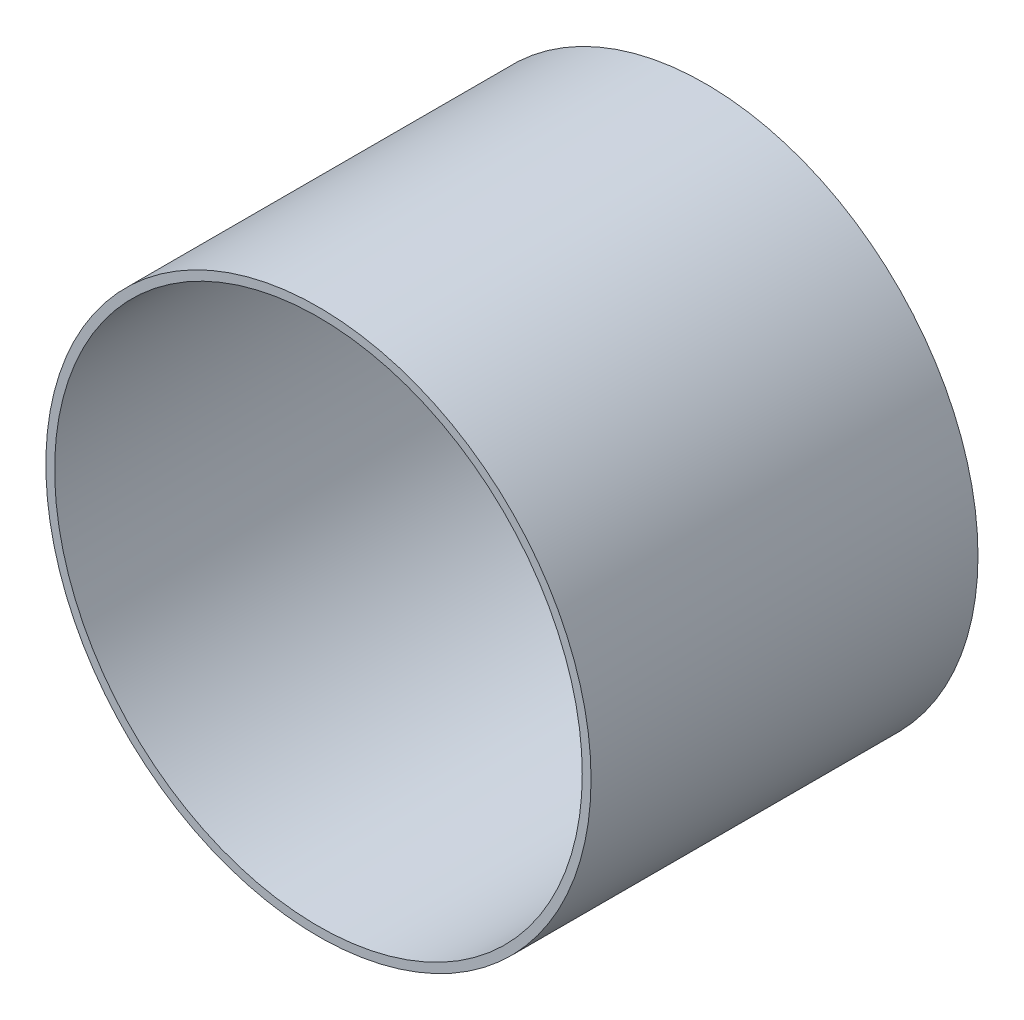
SolidWorks part; units mm, degrees
material "1023 Chapa de acero al carbono (SS)"
ref_plane "Alzado" through (0, 0, 0) normal (0, 0, 1) x (1, 0, 0)
ref_plane "Planta" through (0, 0, 0) normal (0, 1, 0) x (1, 0, 0)
ref_plane "Vista lateral" through (0, 0, 0) normal (1, 0, 0) x (0, 0, -1)
sketch "Croquis1" plane through (0, 0, 0) normal (0, 0, 1) x (1, 0, 0)
  circle A0 centre (0, 0) radius 15
  circle A1 centre (0, 0) radius 15.5
  dimension "D1" = 31
  dimension "D2" = 30
extrude "Saliente-Extruir1" add sketch "Croquis1" along normal blind 22
